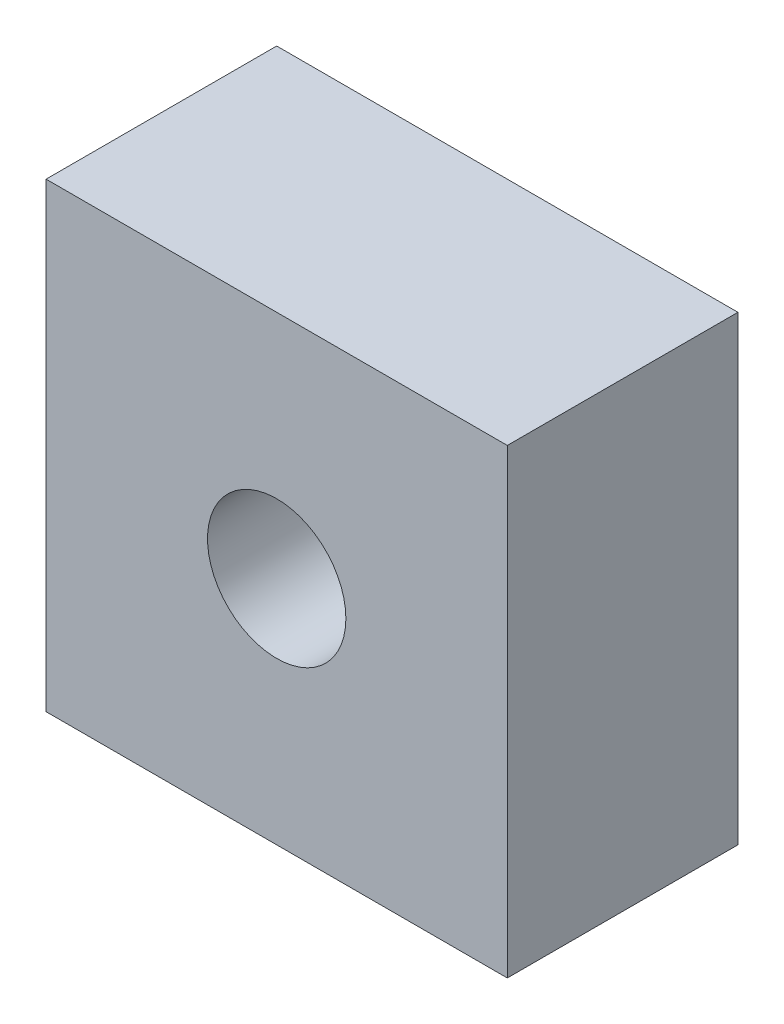
SolidWorks part; units mm, degrees
material "ﾎﾟﾘ塩化ﾋﾞﾆﾙ(PVC)硬質"
ref_plane "正面" through (0, 0, 0) normal (0, 0, 1) x (1, 0, 0)
ref_plane "平面" through (0, 0, 0) normal (0, 1, 0) x (1, 0, 0)
ref_plane "右側面" through (0, 0, 0) normal (1, 0, 0) x (0, 0, -1)
sketch "ｽｹｯﾁ1" plane through (0, 0, 0) normal (0, 0, 1) x (1, 0, 0)
  line L1 (-5, -5) -> (5, -5)
  line L2 (-5, -5) -> (-5, 5)
  line L3 (-5, 5) -> (5, 5)
  line L4 (5, -5) -> (5, 5)
  line L5 (-5, -5) -> (5, 5) construction
  line L6 (-5, 5) -> (5, -5) construction
  circle A0 centre (0, 0) radius 1.5
  point P0 (0, 0)
  dimension "D1" = 3
  dimension "D2" = 10
  dimension "D3" = 10
extrude "ﾎﾞｽ - 押し出し1" add sketch "ｽｹｯﾁ1" along normal blind 5
